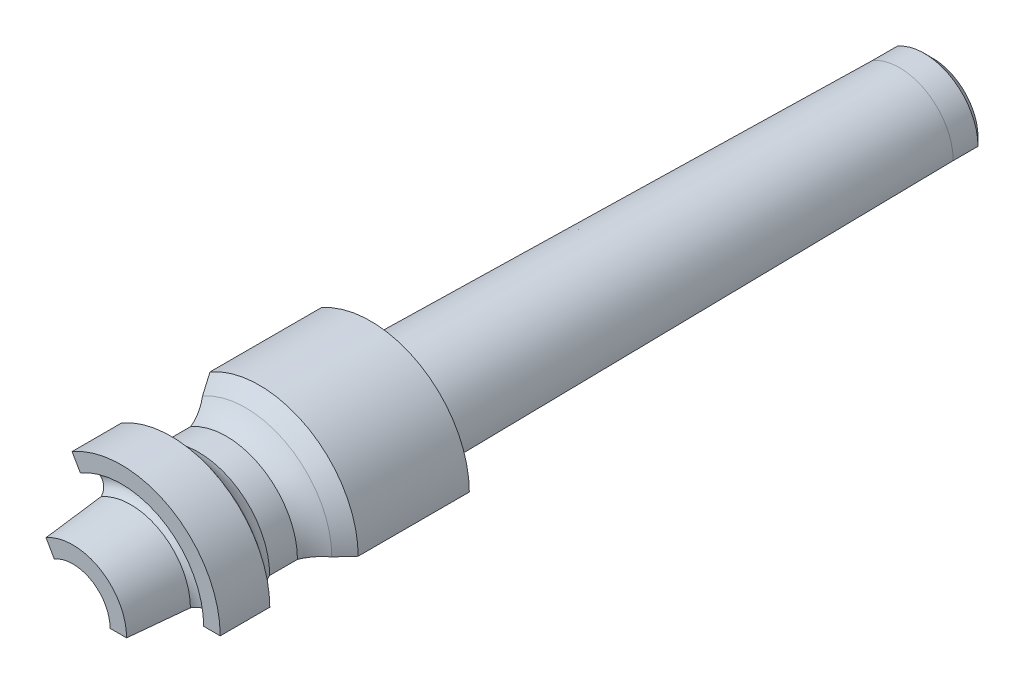
SolidWorks part; units mm, degrees
ref_plane "정면" through (0, 0, 0) normal (0, 0, 1) x (1, 0, 0)
ref_plane "윗면" through (0, 0, 0) normal (0, 1, 0) x (1, 0, 0)
ref_plane "우측면" through (0, 0, 0) normal (1, 0, 0) x (0, 0, -1)
sketch "스케치1" plane through (0, 0, 0) normal (0, 1, 0) x (1, 0, 0)
  line L0 (0, 0) -> (0, -50) construction
  line L1 (0, 0) -> (2.25, 0)
  line L2 (2.25, 0) -> (2.25, -50)
  line L3 (5.975, -31.9934) -> (5.3323, -31.9934)
  line L4 (3.25, -50) -> (3.6031, -46.4945)
  line L5 (4.6062, -46.2217) -> (4.975, -47.0626)
  line L6 (4.975, -47.0626) -> (5.975, -47.0626)
  line L7 (5.975, -47.0626) -> (5.975, -44.0626)
  line L8 (5.975, -44.0626) -> (5.0783, -43.3937)
  line L9 (4.3057, -42.3999) -> (4.3057, -40.7214)
  line L10 (5.975, -38.7175) -> (5.975, -31.9934)
  line L11 (3.8599, -36.6805) -> (3.25, 0)
  line L12 (3.25, 0) -> (2.25, 0)
  line L13 (2.25, -50) -> (0, -50) construction
  line L14 (109.3142, -100.0176) -> (109.3142, -519.351) construction
  line L16 (5.975, -38.7175) -> (5.2136, -39.5517)
  line L21 (2.25, -50) -> (3.25, -50)
  arc A0 (3.6031, -46.4945) -> (4.6062, -46.2217) centre (4.224, -46.797) cw
  arc A1 (5.0783, -43.3937) -> (4.3057, -42.3999) centre (6.4935, -41.4963) cw
  arc A2 (4.3057, -40.7214) -> (5.2136, -39.5517) centre (6.8451, -41.7552) cw
  arc A3 (3.8599, -36.6805) -> (4.7504, -36.6731) centre (4.3051, -36.6731) ccw
  arc A4 (5.3323, -31.9934) -> (4.7504, -36.6731) centre (-12.8081, -32.1138) cw
  dimension "D1" = 11.95
  dimension "D2" = 50
  dimension "D3" = 4.5
  dimension "D4" = 1
  dimension "D5" = 3
  dimension "D6" = 1
  dimension "D7" = 1
revolve "회전1" add sketch "스케치1" angle 120 about L0
sketch "스케치3" plane through (0, 0, 0) normal (0, 1, 0) x (1, 0, 0)
  line L0 (0, 0) -> (0, -50) construction
  line L2 (2.25, 0) -> (1.86, -1)
  line L3 (1.86, -1) -> (2.25, -2)
  line L4 (2.25, 0) -> (2.25, -50) construction
  line L5 (2.25, -2) -> (2.25, 0) construction
  line L6 (2.25, 0) -> (0, 0) construction
  line L7 (2.25, -2) -> (1.86, -3)
  line L8 (1.86, -3) -> (2.25, -4)
  line L9 (2.25, -4) -> (2.25, -2) construction
  line L10 (2.25, -4) -> (1.86, -5)
  line L11 (1.86, -5) -> (2.25, -6)
  line L12 (2.25, -6) -> (2.25, -4) construction
  line L13 (2.25, -6) -> (1.86, -7)
  line L14 (1.86, -7) -> (2.25, -8)
  line L15 (2.25, -8) -> (2.25, -6) construction
  line L16 (2.25, -8) -> (1.86, -9)
  line L17 (1.86, -9) -> (2.25, -10)
  line L18 (2.25, -10) -> (2.25, -8) construction
  line L19 (2.25, -10) -> (1.86, -11)
  line L20 (1.86, -11) -> (2.25, -12)
  line L21 (2.25, -12) -> (2.25, -10) construction
  line L22 (2.25, -12) -> (1.86, -13)
  line L23 (1.86, -13) -> (2.25, -14)
  line L24 (2.25, -14) -> (2.25, -12) construction
  line L25 (2.25, -14) -> (1.86, -15)
  line L26 (1.86, -15) -> (2.25, -16)
  line L27 (2.25, -16) -> (2.25, -14) construction
  line L28 (2.25, -16) -> (1.86, -17)
  line L29 (1.86, -17) -> (2.25, -18)
  line L30 (2.25, -18) -> (2.25, -16) construction
  line L31 (2.25, -18) -> (1.86, -19)
  line L32 (1.86, -19) -> (2.25, -20)
  line L33 (2.25, -20) -> (2.25, -18) construction
  line L34 (2.25, -20) -> (1.86, -21)
  line L35 (1.86, -21) -> (2.25, -22)
  line L36 (2.25, -22) -> (2.25, -20) construction
  line L37 (2.25, -22) -> (1.86, -23)
  line L38 (1.86, -23) -> (2.25, -24)
  line L39 (2.25, -24) -> (2.25, -22) construction
  line L40 (2.25, -24) -> (1.86, -25)
  line L41 (1.86, -25) -> (2.25, -26)
  line L42 (2.25, -26) -> (2.25, -24) construction
  line L43 (2.25, -26) -> (1.86, -27)
  line L44 (1.86, -27) -> (2.25, -28)
  line L45 (2.25, -28) -> (2.25, -26) construction
  line L46 (2.25, -28) -> (1.86, -29)
  line L47 (1.86, -29) -> (2.25, -30)
  line L48 (2.25, -30) -> (2.25, -28) construction
  line L49 (2.25, -30) -> (1.86, -31)
  line L50 (1.86, -31) -> (2.25, -32)
  line L51 (2.25, -32) -> (2.25, -30) construction
  line L52 (2.25, -32) -> (1.86, -33)
  line L53 (1.86, -33) -> (2.25, -34)
  line L54 (2.25, -34) -> (2.25, -32) construction
  line L55 (2.25, -34) -> (1.86, -35)
  line L56 (1.86, -35) -> (2.25, -36)
  line L57 (2.25, -36) -> (2.25, -34) construction
  line L58 (2.25, -36) -> (1.86, -37)
  line L59 (1.86, -37) -> (2.25, -38)
  line L60 (2.25, -38) -> (2.25, -36) construction
  line L61 (2.25, -38) -> (1.86, -39)
  line L62 (1.86, -39) -> (2.25, -40)
  line L63 (2.25, -40) -> (2.25, -38) construction
  line L64 (2.25, -40) -> (1.86, -41)
  line L65 (1.86, -41) -> (2.25, -42)
  line L66 (2.25, -42) -> (2.25, -40) construction
  line L67 (2.25, -42) -> (1.86, -43)
  line L68 (1.86, -43) -> (2.25, -44)
  line L69 (2.25, -44) -> (2.25, -42) construction
  line L70 (2.25, -44) -> (1.86, -45)
  line L71 (1.86, -45) -> (2.25, -46)
  line L72 (2.25, -46) -> (2.25, -44) construction
  line L73 (2.25, -46) -> (1.86, -47)
  line L74 (1.86, -47) -> (2.25, -48)
  line L75 (2.25, -48) -> (2.25, -46) construction
  line L76 (2.25, -48) -> (1.86, -49)
  line L77 (1.86, -49) -> (2.25, -50)
  line L78 (2.25, -50) -> (2.25, -48) construction
  line L79 (2.25, -50) -> (2.4763, -50)
  line L81 (2.4763, -50) -> (2.4763, 0)
  line L82 (3.25, 0) -> (-1.625, 0) construction
  line L83 (2.4763, 0) -> (2.25, 0)
  line L84 (0, -50) -> (2.25, -50) construction
  dimension "D1" = 2
  dimension "D2" = 0.39
  dimension "D3" = 50
  dimension "D4" = 25
revolve "회전2" add sketch "스케치3" angle 120 about L0
sketch "스케치4" plane through (0, 0, 0) normal (0, 1, 0) x (1, 0, 0)
  line L0 (0, 0) -> (0, -60.4353) construction
fillet "필렛27" radius 2 25 edges at (0.93, 1.6108, 49) (0.93, 1.6108, 45) (0.93, 1.6108, 47) (0.93, 1.6108, 1) (0.93, 1.6108, 3) (0.93, 1.6108, 5) (0.93, 1.6108, 7) (0.93, 1.6108, 9) (0.93, 1.6108, 11) (0.93, 1.6108, 13) (0.93, 1.6108, 15) (0.93, 1.6108, 17) (0.93, 1.6108, 19) (0.93, 1.6108, 21) (0.93, 1.6108, 23) (0.93, 1.6108, 25) (0.93, 1.6108, 27) (0.93, 1.6108, 29) (0.93, 1.6108, 31) (0.93, 1.6108, 33) (0.93, 1.6108, 35) (0.93, 1.6108, 37) (0.93, 1.6108, 39) (0.93, 1.6108, 41) (0.93, 1.6108, 43)
sketch "스케치5" plane through (0, 0, 0) normal (0, 0, -1) x (-1, 0, 0)
  line L2 (1.125, 1.9486) -> (1.625, 2.8146)
  line L3 (-3.25, 0) -> (-2.25, 0)
  line L4 (1.125, 1.9486) -> (1.625, 2.8146)
  line L5 (-3.25, 0) -> (-2.25, 0)
  arc A2 (1.125, 1.9486) -> (-2.25, 0) centre (0, 0) ccw
  arc A3 (1.625, 2.8146) -> (-3.25, 0) centre (0, 0) ccw
  arc A4 (1.125, 1.9486) -> (-2.25, 0) centre (0, 0) ccw
  arc A5 (1.625, 2.8146) -> (-3.25, 0) centre (0, 0) ccw
  dimension "D1" = 0
extrude "보스-돌출1" add sketch "스케치5" along normal blind 2
chamfer "모따기1" distance 0.5 angle 45 1 edges at (1.625, 2.8146, -2)
